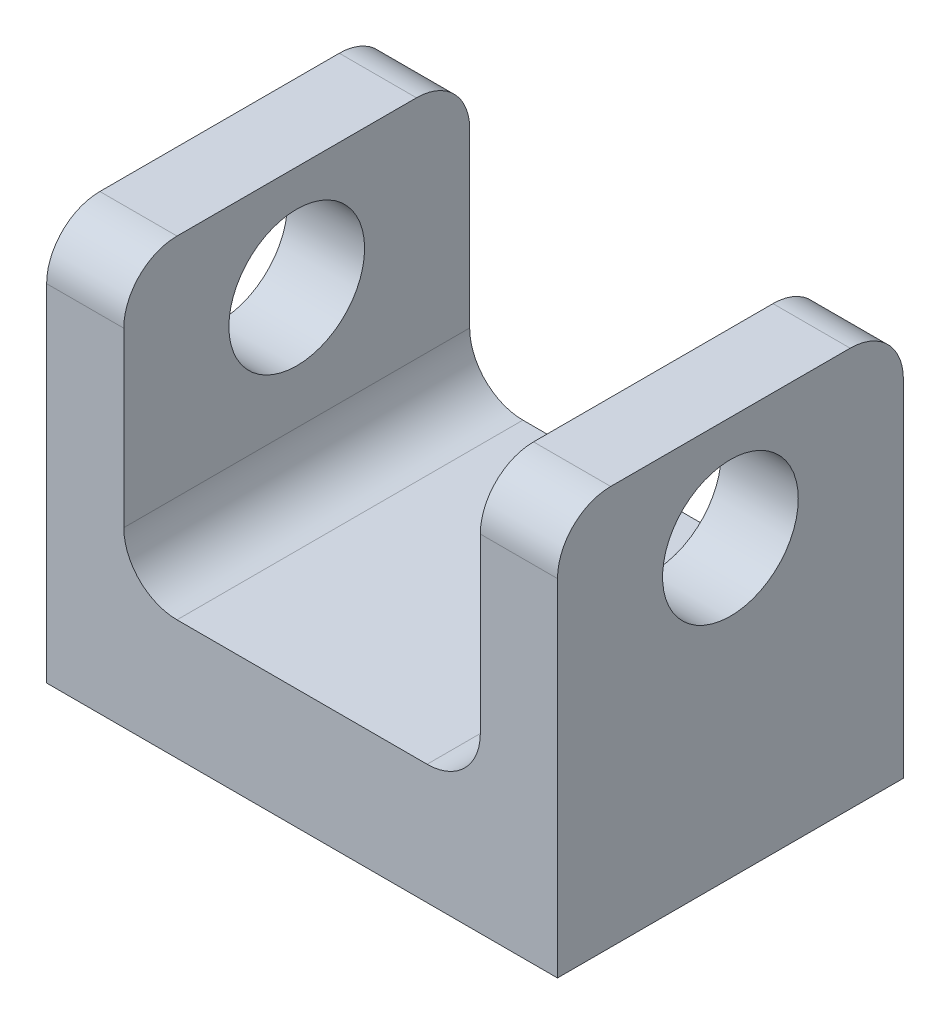
SolidWorks part; units mm, degrees
material "7075-O (SS)"
ref_plane "Front Plane" through (0, 0, 0) normal (0, 0, 1) x (1, 0, 0)
ref_plane "Top Plane" through (0, 0, 0) normal (0, 1, 0) x (1, 0, 0)
ref_plane "Right Plane" through (0, 0, 0) normal (1, 0, 0) x (0, 0, -1)
sketch "Sketch1" plane through (0, 0, 0) normal (0, 0, 1) x (1, 0, 0)
  line L1 (-48, -37.5) -> (48, -37.5)
  line L2 (-48, -37.5) -> (-48, 37.5)
  line L3 (-48, 37.5) -> (48, 37.5)
  line L4 (48, -37.5) -> (48, 37.5)
  line L5 (-48, -37.5) -> (48, 37.5) construction
  line L6 (-48, 37.5) -> (48, -37.5) construction
  point P0 (0, 0)
  dimension "D1" = 96
  dimension "D2" = 75
extrude "Boss-Extrude1" add sketch "Sketch1" along normal blind 65
sketch "Sketch2" plane through (0, 0, 65) normal (0, 0, 1) x (1, 0, 0)
  line L0 (48, 37.5) -> (-48, 37.5) construction
  line L1 (-33.5, -14.9602) -> (33.5, -14.9602)
  line L2 (-33.5, -14.9602) -> (-33.5, 89.9602)
  line L3 (-33.5, 89.9602) -> (33.5, 89.9602)
  line L4 (33.5, -14.9602) -> (33.5, 89.9602)
  line L5 (-33.5, -14.9602) -> (33.5, 89.9602) construction
  line L6 (-33.5, 89.9602) -> (33.5, -14.9602) construction
  point P0 (0, 37.5)
  dimension "D1" = 67
extrude "Cut-Extrude1" cut sketch "Sketch2" against normal through all
sketch "Sketch3" plane through (-33.5, 0, 0) normal (1, 0, 0) x (0, 0, -1)
  line L0 (-32.5, 37.5) -> (-32.5, -14.9602) construction
  line L1 (-65, 37.5) -> (0, 37.5) construction
  line L2 (0, -14.9602) -> (-65, -14.9602) construction
  circle A0 centre (-32.5, 17.8789) radius 12.75
  dimension "D1" = 25.5
extrude "Cut-Extrude2" cut sketch "Sketch3" against normal through all both and the other way through all
fillet "Fillet1" radius 10 6 edges at (33.5, -14.9602, 32.5) (-33.5, -14.9602, 32.5) (40.75, 37.5, 0) (40.75, 37.5, 65) (-40.75, 37.5, 0) (-40.75, 37.5, 65)
